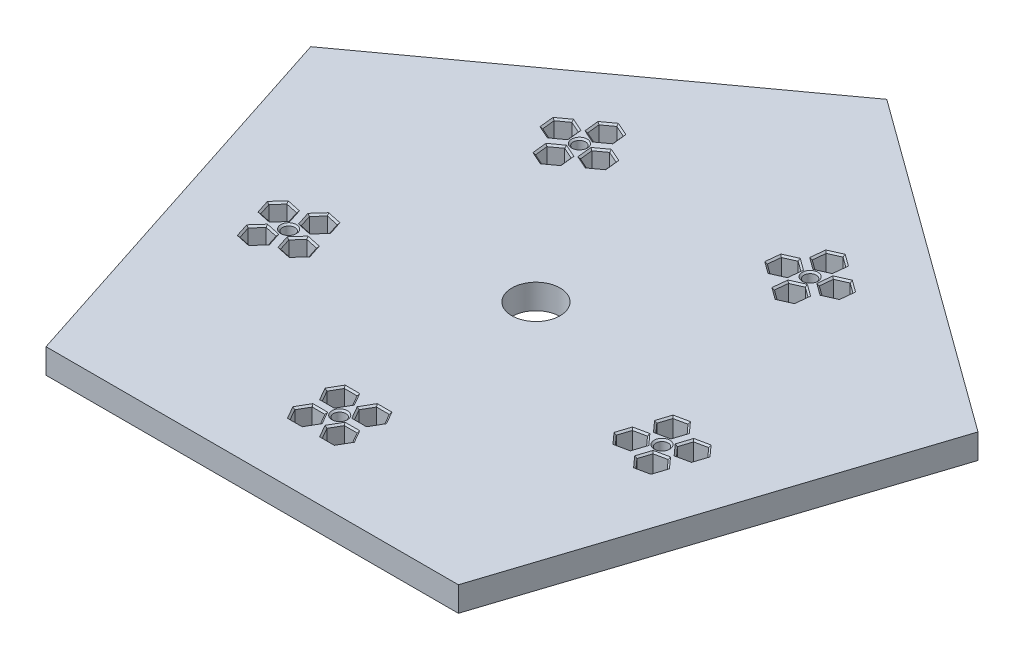
SolidWorks part; units mm, degrees
ref_plane "Front Plane" through (0, 0, 0) normal (0, 0, 1) x (1, 0, 0)
ref_plane "Top Plane" through (0, 0, 0) normal (0, 1, 0) x (1, 0, 0)
ref_plane "Right Plane" through (0, 0, 0) normal (1, 0, 0) x (0, 0, -1)
sketch "Sketch1" plane through (0, 0, 0) normal (0, 1, 0) x (1, 0, 0)
  line L6 (102.7452, 33.3839) -> (0, 108.0327)
  line L7 (0, 108.0327) -> (-102.7452, 33.3839)
  line L8 (-102.7452, 33.3839) -> (-63.5, -87.4003)
  line L9 (-63.5, -87.4003) -> (63.5, -87.4003)
  line L10 (63.5, -87.4003) -> (102.7452, 33.3839)
  circle A0 centre (0, 0) radius 87.4003 construction
  circle A1 centre (0, 0) radius 7.429
  dimension "D1" = 127
extrude "Boss-Extrude1" add sketch "Sketch1" along normal blind 7.62
sketch "Sketch3" plane through (0, 7.62, 0) normal (0, 1, 0) x (1, 0, 0)
  line L1 (-1.0229, -55.499) -> (-2.9879, -52.0954)
  line L2 (-2.9879, -52.0954) -> (-6.9181, -52.0954)
  line L3 (-6.9181, -52.0954) -> (-8.8831, -55.499)
  line L4 (-8.8831, -55.499) -> (-6.9181, -58.9026)
  line L5 (-6.9181, -58.9026) -> (-2.9879, -58.9026)
  line L6 (-2.9879, -58.9026) -> (-1.0229, -55.499)
  line L7 (8.8831, -55.499) -> (6.9181, -52.0954)
  line L8 (6.9181, -52.0954) -> (2.9879, -52.0954)
  line L9 (2.9879, -52.0954) -> (1.0229, -55.499)
  line L10 (1.0229, -55.499) -> (2.9879, -58.9026)
  line L11 (2.9879, -58.9026) -> (6.9181, -58.9026)
  line L12 (6.9181, -58.9026) -> (8.8831, -55.499)
  line L13 (8.8831, -65.405) -> (6.9181, -62.0014)
  line L14 (6.9181, -62.0014) -> (2.9879, -62.0014)
  line L15 (2.9879, -62.0014) -> (1.0229, -65.405)
  line L16 (1.0229, -65.405) -> (2.9879, -68.8086)
  line L17 (2.9879, -68.8086) -> (6.9181, -68.8086)
  line L18 (6.9181, -68.8086) -> (8.8831, -65.405)
  line L19 (-1.0229, -65.405) -> (-2.9879, -62.0014)
  line L20 (-2.9879, -62.0014) -> (-6.9181, -62.0014)
  line L21 (-6.9181, -62.0014) -> (-8.8831, -65.405)
  line L22 (-8.8831, -65.405) -> (-6.9181, -68.8086)
  line L23 (-6.9181, -68.8086) -> (-2.9879, -68.8086)
  line L24 (-2.9879, -68.8086) -> (-1.0229, -65.405)
  circle A0 centre (0, -60.452) radius 1.905
  circle A1 centre (-4.953, -55.499) radius 3.4036 construction
  circle A2 centre (4.953, -55.499) radius 3.4036 construction
  circle A3 centre (4.953, -65.405) radius 3.4036 construction
  circle A4 centre (-4.953, -65.405) radius 3.4036 construction
  dimension "D15" = 3.81
  dimension "D2" = 6.8072
  dimension "D3" = 6.8072
  dimension "D4" = 6.8072
  dimension "D5" = 6.8072
  dimension "D6" = 9.906
  dimension "D7" = 9.906
  dimension "D8" = 9.906
  dimension "D9" = 9.906
  dimension "D10" = 0
  dimension "D11" = 0
  dimension "D12" = 4.953
  dimension "D14" = 4.953
  dimension "D13" = 60.452
  dimension "D16" = 0
extrude "Cut-Extrude1" cut sketch "Sketch3" against normal blind 7.112
chamfer "Chamfer2" distance 0.508 angle 45 25 edges at (0, 7.62, 62.357) (-4.953, 7.62, 58.9026) (-7.9006, 7.62, 57.2008) (-7.9006, 7.62, 53.7972) (-4.953, 7.62, 52.0954) (-2.0054, 7.62, 53.7972) (-2.0054, 7.62, 57.2008) (4.953, 7.62, 58.9026) (2.0054, 7.62, 57.2008) (2.0054, 7.62, 53.7972) (4.953, 7.62, 52.0954) (7.9006, 7.62, 53.7972) (7.9006, 7.62, 57.2008) (4.953, 7.62, 68.8086) (2.0054, 7.62, 67.1068) (2.0054, 7.62, 63.7032) (4.953, 7.62, 62.0014) (7.9006, 7.62, 63.7032) (7.9006, 7.62, 67.1068) (-4.953, 7.62, 68.8086) (-7.9006, 7.62, 67.1068) (-7.9006, 7.62, 63.7032) (-4.953, 7.62, 62.0014) (-2.0054, 7.62, 63.7032) (-2.0054, 7.62, 67.1068)
sketch "Sketch4" plane through (0, 7.62, 0) normal (0, 1, 0) x (1, 0, 0)
  circle A0 centre (4.953, -55.499) radius 2.54
  circle A1 centre (4.953, -65.405) radius 2.54
  circle A2 centre (-4.953, -65.405) radius 2.54
  circle A3 centre (-4.953, -55.499) radius 2.54
  circle A4 centre (0, -60.452) radius 1.905 construction
  circle A5 centre (0, -60.452) radius 1.905 construction
  circle A6 centre (0, -60.452) radius 1.905
  dimension "D6" = 4.953
  dimension "D7" = 5.08
  dimension "D8" = 5.08
  dimension "D9" = 5.08
  dimension "D10" = 5.08
  dimension "D1" = 9.906
  dimension "D2" = 9.906
  dimension "D3" = 9.906
  dimension "D4" = 9.906
  dimension "D5" = 4.953
extrude "Cut-Extrude2" cut sketch "Sketch4" against normal through all
pattern_circular "CirPattern2" count 5 over 360 about axis through (0, 0, 0) along (0, 1, 0) of "Cut-Extrude1", "Chamfer2", "Cut-Extrude2"
equation "\"Standoff\"= 0.268"
equation "\"D2@Sketch3\"=\"Standoff\""
equation "\"D3@Sketch3\"=\"Standoff\""
equation "\"D4@Sketch3\"=\"Standoff\""
equation "\"D5@Sketch3\"=\"Standoff\""
